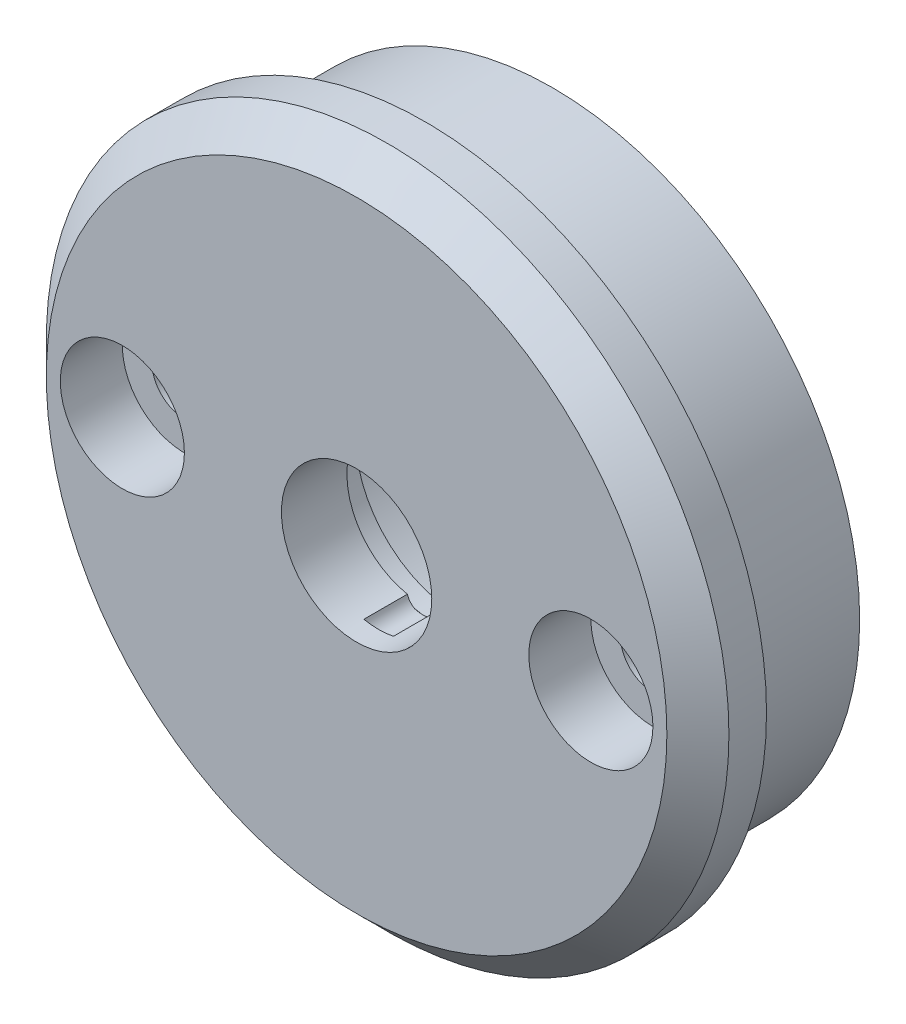
SolidWorks part; units mm, degrees
ref_plane "Front Plane" through (0, 0, 0) normal (0, 0, 1) x (1, 0, 0)
ref_plane "Top Plane" through (0, 0, 0) normal (0, 1, 0) x (1, 0, 0)
ref_plane "Right Plane" through (0, 0, 0) normal (1, 0, 0) x (0, 0, -1)
sketch "Sketch1" plane through (0, 0, 2.5) normal (0, 0, 1) x (1, 0, 0)
  circle A3 centre (0, 0) radius 9.9
extrude "Boss-Extrude1" add sketch "Sketch1" along normal offset from surface (4.1024 mm away) 0.1
sketch "Sketch3" plane through (0, 0, 6.6024) normal (0, 0, 1) x (1, 0, 0)
  circle A0 centre (0, 0) radius 11
  dimension "D1" = 22
extrude "Boss-Extrude2" add sketch "Sketch3" along normal up to surface (2.2114 mm away)
sketch "Sketch4" plane through (0, 0, 0) normal (1, 0, 0) x (0, 0, -1)
  line L4 (-6.03, 3.1505) -> (0, 3.1505) construction
  line L5 (-6.03, 3.1505) -> (0, 3.1505) construction
  line L6 (-6.5024, 2.6737) -> (-6.5024, -2.7026) construction
  line L7 (-6.5024, 2.6737) -> (-6.5024, -2.7026) construction
  line L8 (0.889, 2.2225) -> (-8.8138, 2.2225) construction
  line L9 (0.889, 2.2225) -> (-8.8138, 2.2225) construction
  line L10 (-6.5024, 2.6737) -> (-6.5024, 2.2225) construction
  line L11 (-6.5024, 2.2225) -> (-8.8138, 2.2225) construction
  line L12 (-6.1132, 3.3505) -> (0, 3.3505)
  line L13 (-6.7024, 2.6737) -> (-6.7024, 2.4225)
  line L14 (-6.7024, 2.4225) -> (-8.8138, 2.4225)
  line L15 (-6.6446, 2.8144) -> (-6.7024, 2.6737)
  line L16 (-8.8138, 2.4225) -> (-8.8138, 0)
  line L17 (-8.8138, 0) -> (0, 0)
  line L18 (0, 0) -> (0, 3.3505)
  arc A0 (-6.03, 3.1505) -> (-6.5024, 2.6737) centre (315.2576, -315.6941) ccw construction
  arc A1 (-6.03, 3.1505) -> (-6.5024, 2.6737) centre (315.2576, -315.6941) ccw construction
  arc A2 (-6.1132, 3.3505) -> (-6.6446, 2.8144) centre (315.2576, -315.6941) ccw
  dimension "D1" = 0.2
  dimension "D2" = 0.2
revolve "Cut-Revolve2" cut sketch "Sketch4" angle 360 about L17
sketch "Sketch6" plane through (0, 0, 6.6024) normal (0, 0, -1) x (-1, 0, 0)
  circle A0 centre (0, -2.2225) radius 0.5
  arc A1 (0, -2.2225) -> (0.2536, -2.208) centre (0, 0) ccw construction
  arc A4 (0, -2.2225) -> (0.2536, -2.208) centre (0, 0) ccw construction
  arc A14 (-2.1062, -0.7095) -> (2.1062, -0.7095) centre (0, 0) ccw construction
  arc A15 (-2.1062, -0.7095) -> (2.1062, -0.7095) centre (0, 0) ccw construction
  point P4 (0, -2.2225)
  dimension "D1" = 1
extrude "Cut-Extrude1" cut sketch "Sketch6" against normal blind 1.5 and the other way through all
chamfer "Chamfer1" distance 1 angle 45 1 edges at (11, 0, 8.8138)
sketch "Sketch7" plane through (0, 0, 8.8138) normal (0, 0, 1) x (1, 0, 0)
  line L1 (0, 0) -> (-7.5495, 0.0859) construction
  line L2 (0, 0) -> (7.55, 0) construction
  circle A0 centre (-7.5495, 0.0859) radius 2
  circle A1 centre (7.55, 0) radius 2
  dimension "D1" = 4
  dimension "D2" = 7.55
extrude "Cut-Extrude2" cut sketch "Sketch7" against normal blind 2
sketch "Sketch8" plane through (0, 0, 6.8138) normal (0, 0, 1) x (1, 0, 0)
  circle A0 centre (-7.5495, 0.0859) radius 1.05
  circle A1 centre (7.55, 0) radius 1.05
  circle A2 centre (7.55, 0) radius 2 construction
  circle A3 centre (-7.5495, 0.0859) radius 2 construction
  dimension "D1" = 2.1
extrude "Cut-Extrude3" cut sketch "Sketch8" against normal through all
sketch "Sketch9" plane through (0, 0, 2.5) normal (0, 0, -1) x (-1, 0, 0)
  line L0 (6.503, 0) -> (6.003, 0) construction
  circle A0 centre (0, 0) radius 6.003
  circle A1 centre (7.5495, 0.0859) radius 1.05 construction
  circle A2 centre (0, 0) radius 3.3505 construction
  dimension "D1" = 0.5
extrude "Cut-Extrude4" cut sketch "Sketch9" against normal blind 3 contours A0
